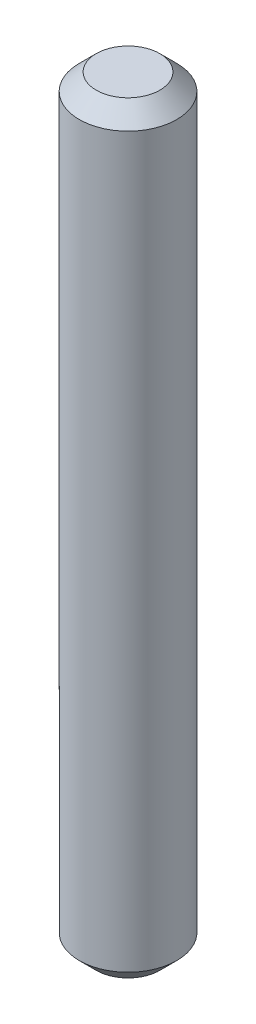
SolidWorks part; units mm, degrees
material "PBT General Purpose"
ref_plane "Front Plane" through (0, 0, 0) normal (0, 0, 1) x (1, 0, 0)
ref_plane "Top Plane" through (0, 0, 0) normal (0, 1, 0) x (1, 0, 0)
ref_plane "Right Plane" through (0, 0, 0) normal (1, 0, 0) x (0, 0, -1)
sketch "Sketch1" plane through (0, 0, 0) normal (0, 1, 0) x (1, 0, 0)
  circle A0 centre (0, 0) radius 2.875
  dimension "D1" = 5.75
extrude "Boss-Extrude1" add sketch "Sketch1" along normal mid plane 45
chamfer "Chamfer1" distance 1 angle 45 2 edges at (0, 22.5, 2.875) (0, -22.5, 2.875)
